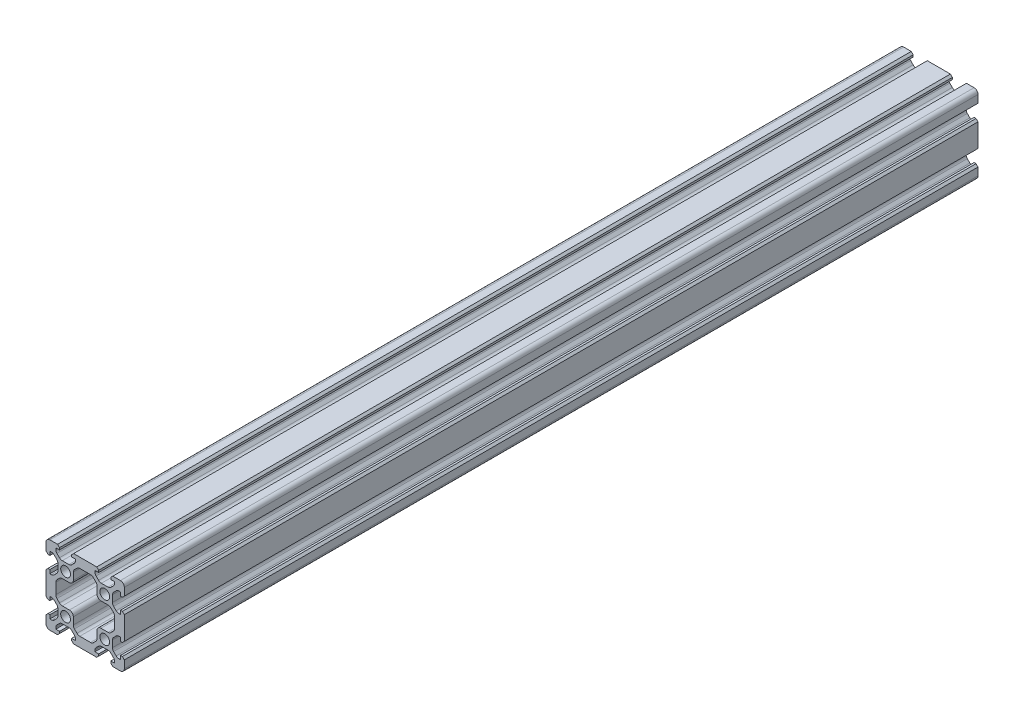
SolidWorks part; units mm, degrees
ref_plane "Front Plane" through (0, 0, 0) normal (0, 0, 1) x (1, 0, 0)
ref_plane "Top Plane" through (0, 0, 0) normal (0, 1, 0) x (1, 0, 0)
ref_plane "Right Plane" through (0, 0, 0) normal (1, 0, 0) x (0, 0, -1)
sketch "Sketch1" plane through (0, 0, 0) normal (0, 0, 1) x (1, 0, 0)
  point P0 (6.9, 0)
  point P1 (0, 6.9)
  point P2 (10, 0)
  point P5 (13.1, 0)
  point P6 (0, 0)
  point P8 (0, 13.1)
  point P9 (-13.1, 0)
  point P14 (0, 0)
  point P15 (0, 0)
  point P19 (0, 0)
  point P21 (10, 0)
  point P22 (10, 0)
  point P23 (6.9, 0)
  point P102 (-6.9, 0)
  line B0 (-4.1716, -14.4142) -> (-5.4621, -13.1236)
  line B1 (-2.7574, -15) -> (2.7574, -15)
  line B2 (-11.7094, -6.0479) -> (-8.0479, -6.0479)
  line B3 (-6.0479, -8.0479) -> (-6.0479, -11.7094)
  line B4 (-13.1236, -5.4621) -> (-14.4142, -4.1716)
  line B5 (-13.1, -19) -> (-14.1, -20)
  line B6 (5.9, -20) -> (-5.9, -20)
  line B7 (-5.9, -20) -> (-6.9, -19)
  line B8 (-14.4142, -15.8284) -> (-13.1236, -14.5379)
  line B9 (-15, -17.2426) -> (-15, -18)
  line B10 (-13.1, -18) -> (-15, -18)
  line B11 (-5, -17.2426) -> (-5, -18)
  line B12 (-5, -18) -> (-6.9, -18)
  line B13 (-6.9, -18) -> (-6.9, -19)
  line B14 (-13.1, -18) -> (-13.1, -19)
  line B15 (-8.2906, -13.9521) -> (-11.7094, -13.9521)
  line B16 (-14.1, -20) -> (-18, -20)
  line B17 (-6.8764, -14.5379) -> (-5.5858, -15.8284)
  line B18 (-19, -6.9) -> (-20, -5.9)
  line B19 (-20, -18) -> (-20, -14.1)
  line B20 (-20, -14.1) -> (-19, -13.1)
  line B21 (-15.8284, -5.5858) -> (-14.5379, -6.8764)
  line B22 (-17.2426, -5) -> (-18, -5)
  line B23 (-18, -6.9) -> (-18, -5)
  line B24 (-17.2426, -15) -> (-18, -15)
  line B25 (-18, -15) -> (-18, -13.1)
  line B26 (-18, -13.1) -> (-19, -13.1)
  line B27 (-18, -6.9) -> (-19, -6.9)
  line B28 (-13.9521, -11.7094) -> (-13.9521, -8.2906)
  line B29 (-14.5379, -13.1236) -> (-15.8284, -14.4142)
  line B30 (-2.7574, 15) -> (2.7574, 15)
  line B31 (-14.4142, 4.1716) -> (-13.1236, 5.4621)
  line B32 (-15, 2.7574) -> (-15, -2.7574)
  line B33 (-6.0479, 11.7094) -> (-6.0479, 8.0479)
  line B34 (-8.0479, 6.0479) -> (-11.7094, 6.0479)
  line B35 (-5.4621, 13.1236) -> (-4.1716, 14.4142)
  line B36 (-19, 13.1) -> (-20, 14.1)
  line B37 (-20, -5.9) -> (-20, 5.9)
  line B38 (-20, 5.9) -> (-19, 6.9)
  line B39 (-15.8284, 14.4142) -> (-14.5379, 13.1236)
  line B40 (-17.2426, 15) -> (-18, 15)
  line B41 (-18, 13.1) -> (-18, 15)
  line B42 (-17.2426, 5) -> (-18, 5)
  line B43 (-18, 5) -> (-18, 6.9)
  line B44 (-18, 6.9) -> (-19, 6.9)
  line B45 (-18, 13.1) -> (-19, 13.1)
  line B46 (-13.9521, 8.2906) -> (-13.9521, 11.7094)
  line B47 (-20, 14.1) -> (-20, 18)
  line B48 (-14.5379, 6.8764) -> (-15.8284, 5.5858)
  line B49 (-6.9, 19) -> (-5.9, 20)
  line B50 (-18, 20) -> (-14.1, 20)
  line B51 (-14.1, 20) -> (-13.1, 19)
  line B52 (-5.5858, 15.8284) -> (-6.8764, 14.5379)
  line B53 (-5, 17.2426) -> (-5, 18)
  line B54 (-6.9, 18) -> (-5, 18)
  line B55 (-15, 17.2426) -> (-15, 18)
  line B56 (-15, 18) -> (-13.1, 18)
  line B57 (-13.1, 18) -> (-13.1, 19)
  line B58 (-6.9, 18) -> (-6.9, 19)
  line B59 (-11.7094, 13.9521) -> (-8.2906, 13.9521)
  line B60 (5.9, 20) -> (-5.9, 20)
  line B61 (-13.1236, 14.5379) -> (-14.4142, 15.8284)
  line B62 (15, 2.7574) -> (15, -2.7574)
  line B63 (4.1716, 14.4142) -> (5.4621, 13.1236)
  line B64 (11.7094, 6.0479) -> (8.0479, 6.0479)
  line B65 (6.0479, 8.0479) -> (6.0479, 11.7094)
  line B66 (13.1236, 5.4621) -> (14.4142, 4.1716)
  line B67 (13.1, 19) -> (14.1, 20)
  line B68 (5.9, 20) -> (6.9, 19)
  line B69 (14.4142, 15.8284) -> (13.1236, 14.5379)
  line B70 (15, 17.2426) -> (15, 18)
  line B71 (13.1, 18) -> (15, 18)
  line B72 (5, 17.2426) -> (5, 18)
  line B73 (5, 18) -> (6.9, 18)
  line B74 (6.9, 18) -> (6.9, 19)
  line B75 (13.1, 18) -> (13.1, 19)
  line B76 (8.2906, 13.9521) -> (11.7094, 13.9521)
  line B77 (14.1, 20) -> (18, 20)
  line B78 (6.8764, 14.5379) -> (5.5858, 15.8284)
  line B79 (19, 6.9) -> (20, 5.9)
  line B80 (20, 18) -> (20, 14.1)
  line B81 (20, 14.1) -> (19, 13.1)
  line B82 (15.8284, 5.5858) -> (14.5379, 6.8764)
  line B83 (17.2426, 5) -> (18, 5)
  line B84 (18, 6.9) -> (18, 5)
  line B85 (17.2426, 15) -> (18, 15)
  line B86 (18, 15) -> (18, 13.1)
  line B87 (18, 13.1) -> (19, 13.1)
  line B88 (18, 6.9) -> (19, 6.9)
  line B89 (13.9521, 11.7094) -> (13.9521, 8.2906)
  line B90 (20, -5.9) -> (20, 5.9)
  line B91 (14.5379, 13.1236) -> (15.8284, 14.4142)
  line B92 (14.4142, -4.1716) -> (13.1236, -5.4621)
  line B93 (6.0479, -11.7094) -> (6.0479, -8.0479)
  line B94 (8.0479, -6.0479) -> (11.7094, -6.0479)
  line B95 (5.4621, -13.1236) -> (4.1716, -14.4142)
  line B96 (19, -13.1) -> (20, -14.1)
  line B97 (20, -5.9) -> (19, -6.9)
  line B98 (15.8284, -14.4142) -> (14.5379, -13.1236)
  line B99 (17.2426, -15) -> (18, -15)
  line B100 (18, -13.1) -> (18, -15)
  line B101 (17.2426, -5) -> (18, -5)
  line B102 (18, -5) -> (18, -6.9)
  line B103 (18, -6.9) -> (19, -6.9)
  line B104 (18, -13.1) -> (19, -13.1)
  line B105 (13.9521, -8.2906) -> (13.9521, -11.7094)
  line B106 (20, -14.1) -> (20, -18)
  line B107 (14.5379, -6.8764) -> (15.8284, -5.5858)
  line B108 (6.9, -19) -> (5.9, -20)
  line B109 (18, -20) -> (14.1, -20)
  line B110 (14.1, -20) -> (13.1, -19)
  line B111 (5.5858, -15.8284) -> (6.8764, -14.5379)
  line B112 (5, -17.2426) -> (5, -18)
  line B113 (6.9, -18) -> (5, -18)
  line B114 (15, -17.2426) -> (15, -18)
  line B115 (15, -18) -> (13.1, -18)
  line B116 (13.1, -18) -> (13.1, -19)
  line B117 (6.9, -18) -> (6.9, -19)
  line B118 (11.7094, -13.9521) -> (8.2906, -13.9521)
  line B119 (13.1236, -14.5379) -> (14.4142, -15.8284)
  circle B120 centre (-10, -10) radius 2.5
  arc B121 (-14.5379, -6.8764) -> (-13.9521, -8.2906) centre (-15.9521, -8.2906) cw
  arc B122 (-15.8284, -5.5858) -> (-17.2426, -5) centre (-17.2426, -7) ccw
  arc B123 (-15, -2.7574) -> (-14.4142, -4.1716) centre (-13, -2.7574) ccw
  arc B124 (6.0479, 8.0479) -> (8.0479, 6.0479) centre (8.0479, 8.0479) ccw
  arc B125 (8.0479, -6.0479) -> (6.0479, -8.0479) centre (8.0479, -8.0479) ccw
  arc B126 (-4.1716, -14.4142) -> (-2.7574, -15) centre (-2.7574, -13) ccw
  arc B127 (-5, -17.2426) -> (-5.5858, -15.8284) centre (-7, -17.2426) ccw
  arc B128 (-14.4142, -15.8284) -> (-15, -17.2426) centre (-13, -17.2426) ccw
  arc B129 (-17.2426, -15) -> (-15.8284, -14.4142) centre (-17.2426, -13) ccw
  arc B130 (-13.9521, -11.7094) -> (-14.5379, -13.1236) centre (-15.9521, -11.7094) cw
  arc B131 (-13.1236, -14.5379) -> (-11.7094, -13.9521) centre (-11.7094, -15.9521) cw
  arc B132 (-8.2906, -13.9521) -> (-6.8764, -14.5379) centre (-8.2906, -15.9521) cw
  arc B133 (-5.4621, -13.1236) -> (-6.0479, -11.7094) centre (-4.0479, -11.7094) cw
  arc B134 (-6.0479, -8.0479) -> (-8.0479, -6.0479) centre (-8.0479, -8.0479) ccw
  arc B135 (-6.0479, 8.0479) -> (-8.0479, 6.0479) centre (-8.0479, 8.0479) cw
  arc B136 (-11.7094, -6.0479) -> (-13.1236, -5.4621) centre (-11.7094, -4.0479) cw
  arc B137 (-18, -20) -> (-20, -18) centre (-18, -18) cw
  circle B138 centre (-10, 10) radius 2.5
  arc B139 (-6.8764, 14.5379) -> (-8.2906, 13.9521) centre (-8.2906, 15.9521) cw
  arc B140 (-5.5858, 15.8284) -> (-5, 17.2426) centre (-7, 17.2426) ccw
  arc B141 (-2.7574, 15) -> (-4.1716, 14.4142) centre (-2.7574, 13) ccw
  arc B142 (-14.4142, 4.1716) -> (-15, 2.7574) centre (-13, 2.7574) ccw
  arc B143 (-17.2426, 5) -> (-15.8284, 5.5858) centre (-17.2426, 7) ccw
  arc B144 (-15.8284, 14.4142) -> (-17.2426, 15) centre (-17.2426, 13) ccw
  arc B145 (-15, 17.2426) -> (-14.4142, 15.8284) centre (-13, 17.2426) ccw
  arc B146 (-11.7094, 13.9521) -> (-13.1236, 14.5379) centre (-11.7094, 15.9521) cw
  arc B147 (-14.5379, 13.1236) -> (-13.9521, 11.7094) centre (-15.9521, 11.7094) cw
  arc B148 (-13.9521, 8.2906) -> (-14.5379, 6.8764) centre (-15.9521, 8.2906) cw
  arc B149 (-13.1236, 5.4621) -> (-11.7094, 6.0479) centre (-11.7094, 4.0479) cw
  arc B150 (-6.0479, 11.7094) -> (-5.4621, 13.1236) centre (-4.0479, 11.7094) cw
  arc B151 (-20, 18) -> (-18, 20) centre (-18, 18) cw
  circle B152 centre (10, 10) radius 2.5
  arc B153 (14.5379, 6.8764) -> (13.9521, 8.2906) centre (15.9521, 8.2906) cw
  arc B154 (15.8284, 5.5858) -> (17.2426, 5) centre (17.2426, 7) ccw
  arc B155 (15, 2.7574) -> (14.4142, 4.1716) centre (13, 2.7574) ccw
  arc B156 (4.1716, 14.4142) -> (2.7574, 15) centre (2.7574, 13) ccw
  arc B157 (5, 17.2426) -> (5.5858, 15.8284) centre (7, 17.2426) ccw
  arc B158 (14.4142, 15.8284) -> (15, 17.2426) centre (13, 17.2426) ccw
  arc B159 (17.2426, 15) -> (15.8284, 14.4142) centre (17.2426, 13) ccw
  arc B160 (13.9521, 11.7094) -> (14.5379, 13.1236) centre (15.9521, 11.7094) cw
  arc B161 (13.1236, 14.5379) -> (11.7094, 13.9521) centre (11.7094, 15.9521) cw
  arc B162 (8.2906, 13.9521) -> (6.8764, 14.5379) centre (8.2906, 15.9521) cw
  arc B163 (5.4621, 13.1236) -> (6.0479, 11.7094) centre (4.0479, 11.7094) cw
  arc B164 (11.7094, 6.0479) -> (13.1236, 5.4621) centre (11.7094, 4.0479) cw
  arc B165 (18, 20) -> (20, 18) centre (18, 18) cw
  circle B166 centre (10, -10) radius 2.5
  arc B167 (6.8764, -14.5379) -> (8.2906, -13.9521) centre (8.2906, -15.9521) cw
  arc B168 (5.5858, -15.8284) -> (5, -17.2426) centre (7, -17.2426) ccw
  arc B169 (2.7574, -15) -> (4.1716, -14.4142) centre (2.7574, -13) ccw
  arc B170 (14.4142, -4.1716) -> (15, -2.7574) centre (13, -2.7574) ccw
  arc B171 (17.2426, -5) -> (15.8284, -5.5858) centre (17.2426, -7) ccw
  arc B172 (15.8284, -14.4142) -> (17.2426, -15) centre (17.2426, -13) ccw
  arc B173 (15, -17.2426) -> (14.4142, -15.8284) centre (13, -17.2426) ccw
  arc B174 (11.7094, -13.9521) -> (13.1236, -14.5379) centre (11.7094, -15.9521) cw
  arc B175 (14.5379, -13.1236) -> (13.9521, -11.7094) centre (15.9521, -11.7094) cw
  arc B176 (13.9521, -8.2906) -> (14.5379, -6.8764) centre (15.9521, -8.2906) cw
  arc B177 (13.1236, -5.4621) -> (11.7094, -6.0479) centre (11.7094, -4.0479) cw
  arc B178 (6.0479, -11.7094) -> (5.4621, -13.1236) centre (4.0479, -11.7094) cw
  arc B179 (20, -18) -> (18, -20) centre (18, -18) cw
sketch_block_instance "4040-1"
sketch_block "4040" parameters "D1"=2, "D2"=2
extrude "Boss-Extrude1" add sketch "Sketch1" along normal blind 436
